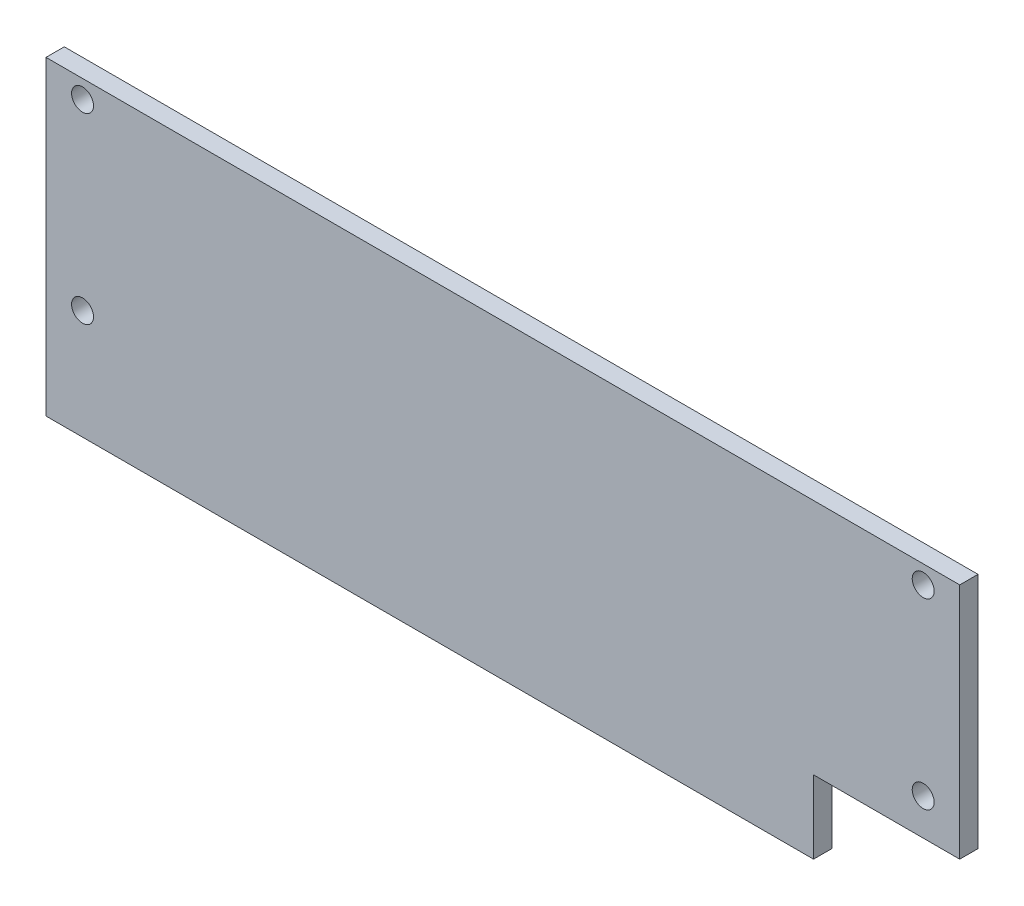
SolidWorks part; units mm, degrees
ref_plane "Plan de face" through (0, 0, 0) normal (0, 0, 1) x (1, 0, 0)
ref_plane "Plan de dessus" through (0, 0, 0) normal (0, 1, 0) x (1, 0, 0)
ref_plane "Plan de droite" through (0, 0, 0) normal (1, 0, 0) x (0, 0, -1)
sketch "Esquisse1" plane through (0, 0, 0) normal (0, 0, 1) x (1, 0, 0)
  line L0 (125, 0) -> (125, -85) construction
  line L1 (0, 0) -> (250, 0)
  line L2 (0, 0) -> (0, -85)
  line L3 (0, -85) -> (250, -85)
  line L4 (250, 0) -> (250, -85)
  circle A0 centre (10, -5) radius 3
  circle A1 centre (10, -55) radius 3
  circle A2 centre (240, -55) radius 3
  circle A3 centre (240, -5) radius 3
  dimension "D3" = 6
  dimension "D4" = 6
  dimension "D1" = 250
  dimension "D2" = 85
  dimension "D5" = 5
  dimension "D6" = 10
  dimension "D7" = 30
  dimension "D8" = 10
extrude "Boss.-Extru.1" add sketch "Esquisse1" along normal blind 5
sketch "Esquisse2" plane through (0, 0, 0) normal (0, 0, -1) x (-1, 0, 0)
  line L0 (-210, -85) -> (-210, -65)
  line L1 (0, -85) -> (-250, -85) construction
  line L2 (-210, -65) -> (-250, -65)
  line L3 (-250, -85) -> (-250, 0) construction
  line L4 (-210, -85) -> (-250, -85)
  line L5 (-250, -85) -> (-250, -65)
  dimension "D1" = 40
  dimension "D2" = 20
extrude "Enlèv. mat.-Extru.1" cut sketch "Esquisse2" against normal blind 10
